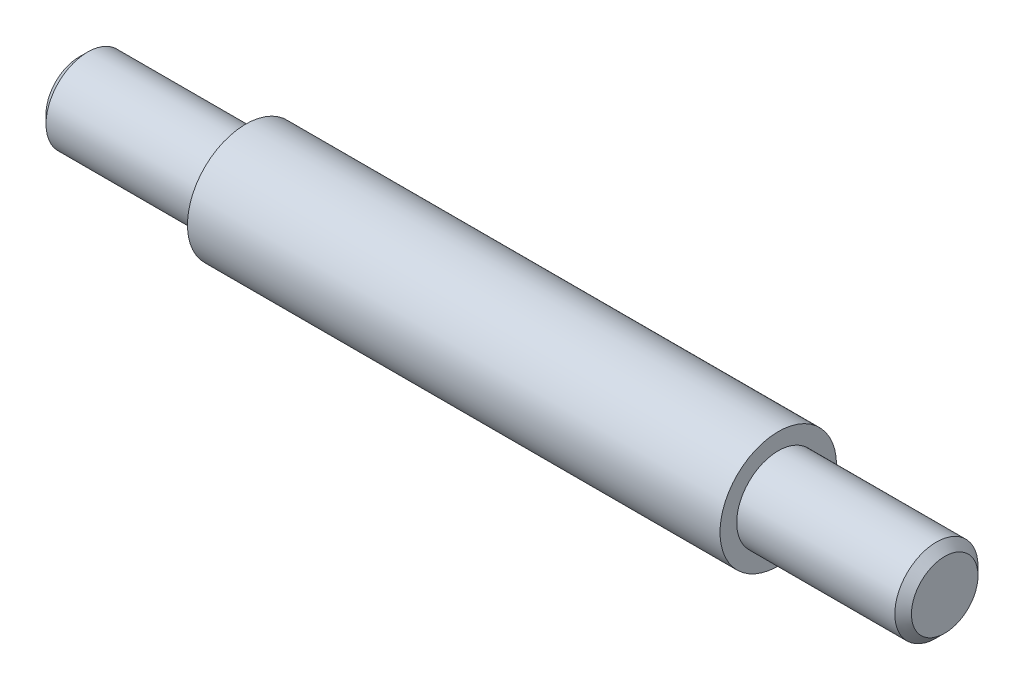
SolidWorks part; units mm, degrees
ref_plane "Piano frontale" through (0, 0, 0) normal (0, 0, 1) x (1, 0, 0)
ref_plane "Piano superiore" through (0, 0, 0) normal (0, 1, 0) x (1, 0, 0)
ref_plane "Piano destro" through (0, 0, 0) normal (1, 0, 0) x (0, 0, -1)
sketch "Schizzo1" plane through (0, 0, 0) normal (1, 0, 0) x (0, 0, -1)
  circle A0 centre (-80, 0) radius 3.5
  dimension "D1" = 7
extrude "Estrusione-Estrusione1" add sketch "Schizzo1" along normal mid plane 32
sketch "Schizzo2" plane through (16, 0, 0) normal (1, 0, 0) x (0, 0, -1)
  circle A0 centre (-80, 0) radius 2.5
  dimension "D1" = 5
extrude "Estrusione-Estrusione2" add sketch "Schizzo2" along normal blind 10
sketch "Schizzo3" plane through (-16, 0, 0) normal (-1, 0, 0) x (0, 0, 1)
  circle A0 centre (80, 0) radius 2.5
  dimension "D1" = 5
extrude "Estrusione-Estrusione3" add sketch "Schizzo3" along normal blind 10
chamfer "Smusso1" distance 0.5 angle 45 2 edges at (-26, 0, 82.5) (26, 0, 77.5)
